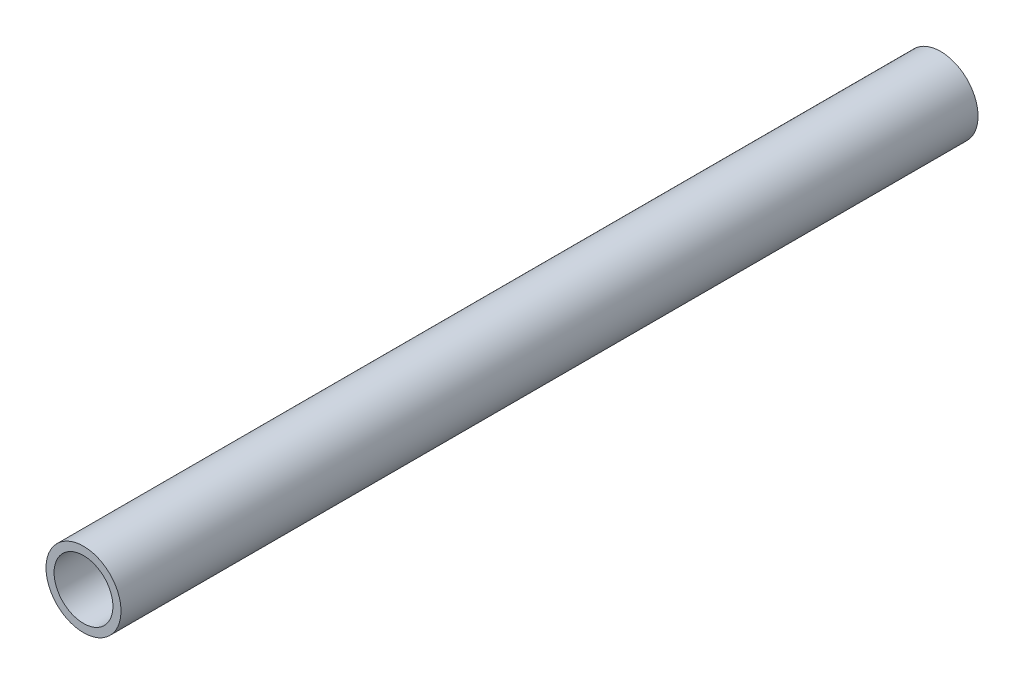
SolidWorks part; units mm, degrees
ref_plane "Front Plane" through (0, 0, 0) normal (0, 0, 1) x (1, 0, 0)
ref_plane "Top Plane" through (0, 0, 0) normal (0, 1, 0) x (1, 0, 0)
ref_plane "Right Plane" through (0, 0, 0) normal (1, 0, 0) x (0, 0, -1)
sketch "Sketch1" plane through (0, 0, 0) normal (0, 0, 1) x (1, 0, 0)
  circle A0 centre (0, 0) radius 10.4648
  circle A1 centre (0, 0) radius 13.335
  dimension "D1" = 2.8702
  dimension "D2" = 26.67
extrude "Boss-Extrude1" add sketch "Sketch1" along normal blind 304.8
